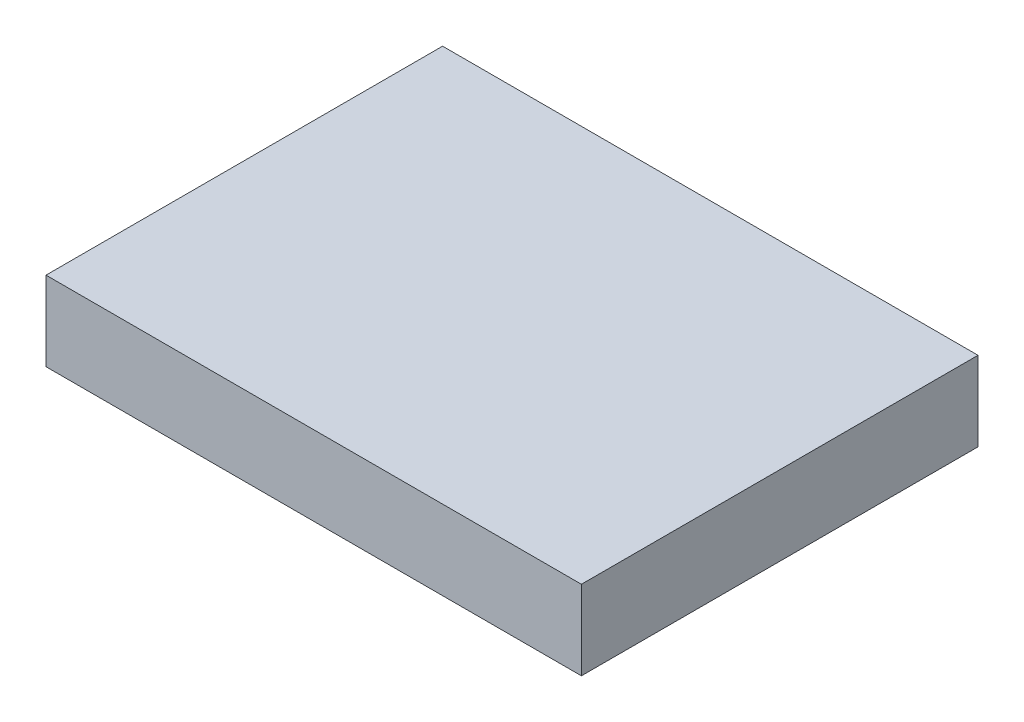
SolidWorks part; units mm, degrees
ref_plane "Front Plane" through (0, 0, 0) normal (0, 0, 1) x (1, 0, 0)
ref_plane "Top Plane" through (0, 0, 0) normal (0, 1, 0) x (1, 0, 0)
ref_plane "Right Plane" through (0, 0, 0) normal (1, 0, 0) x (0, 0, -1)
sketch "Sketch1" plane through (0, 0, 0) normal (0, 1, 0) x (1, 0, 0)
  line L0 (0, 0) -> (0, 20)
  line L1 (0, 0) -> (27, 0)
  line L2 (0, 20) -> (27, 20)
  line L3 (27, 0) -> (27, 20)
  dimension "D1" = 27
  dimension "D2" = 20
extrude "Boss-Extrude1" add sketch "Sketch1" along normal blind 4 contours L1 L3 L2 L0
